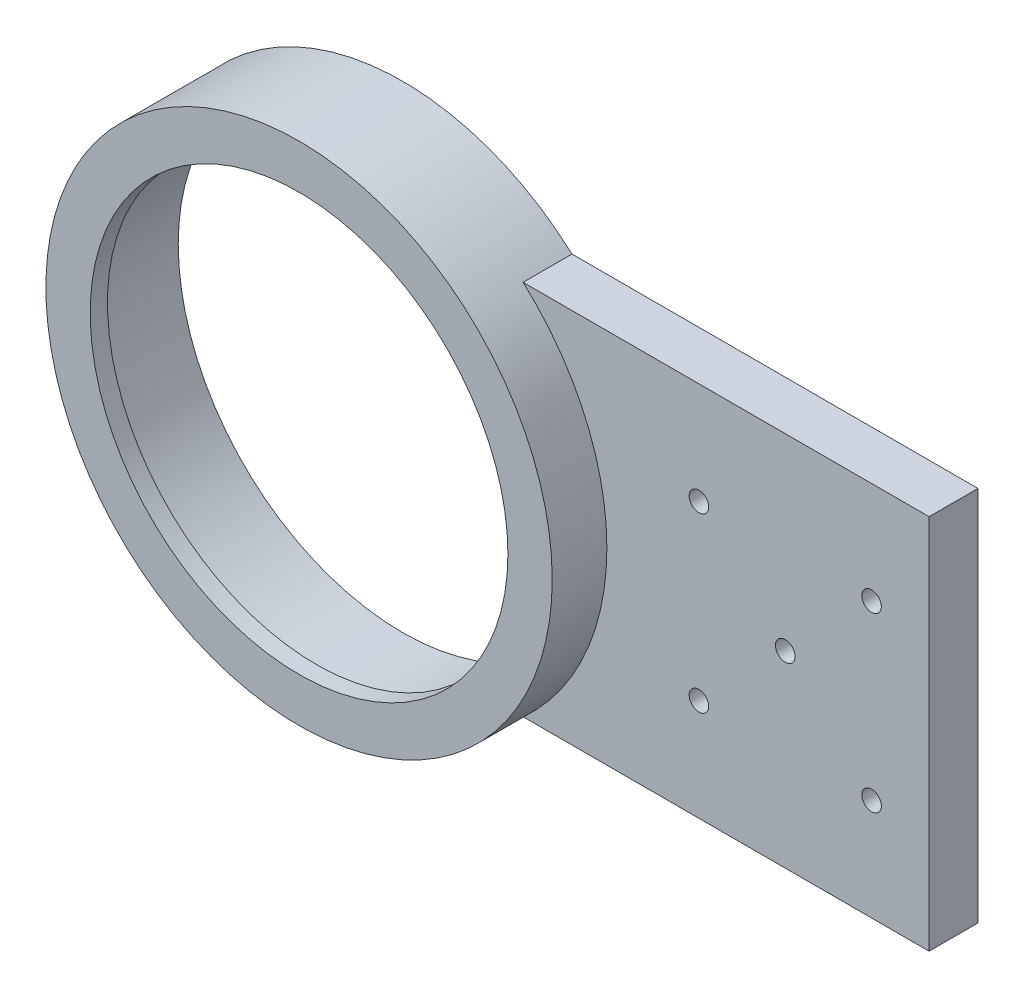
SolidWorks part; units mm, degrees
material "6063-T5"
ref_plane "Front" through (0, 0, 0) normal (0, 0, 1) x (1, 0, 0)
ref_plane "Top" through (0, 0, 0) normal (0, 1, 0) x (1, 0, 0)
ref_plane "Right" through (0, 0, 0) normal (1, 0, 0) x (0, 0, -1)
sketch "Croquis1" plane through (0, 0, 0) normal (0, 0, 1) x (1, 0, 0)
  circle A0 centre (0, 0) radius 36.3
  circle A1 centre (0, 0) radius 44
  dimension "D1" = 72.6
  dimension "D2" = 88
extrude "Saliente-Extruir1" add sketch "Croquis1" along normal blind 3
sketch "Croquis2" plane through (0, 0, 0) normal (0, 0, -1) x (-1, 0, 0)
  circle A0 centre (0, 0) radius 39
  circle A1 centre (0, 0) radius 44 construction
  circle A2 centre (0, 0) radius 44
  dimension "D1" = 78
extrude "Saliente-Extruir2" add sketch "Croquis2" along normal blind 15
sketch "Croquis3" plane through (0, 0, -15) normal (0, 0, -1) x (-1, 0, 0)
  line L0 (-29.4399, 32.7) -> (-100, 32.7)
  line L1 (-100, 32.7) -> (-100, -32.7)
  line L2 (-100, -32.7) -> (-29.4399, -32.7)
  line L3 (10.5108, 0) -> (-10.5108, 0) construction
  line L4 (0, 10.5108) -> (0, -10.5108) construction
  circle A0 centre (0, 0) radius 44 construction
  arc A1 (-29.4399, 32.7) -> (-29.4399, -32.7) centre (0, 0) ccw
  point P9 (-100, 0)
  dimension "D1" = 65.4
  dimension "D2" = 100
extrude "Saliente-Extruir3" add sketch "Croquis3" against normal blind 8.5
hole_wizard "Taladro de margen para M31" positions "Croquis4" profile "Croquis5" hole size "M3" standard "Ansi Metric" end condition up to next
sketch "Croquis4" plane through (0, 0, -15) normal (0, 0, -1) x (-1, 0, 0)
  line L1 (-60, -15) -> (-90, -15) construction
  line L2 (-60, -15) -> (-60, 15) construction
  line L3 (-60, 15) -> (-90, 15) construction
  line L4 (-90, -15) -> (-90, 15) construction
  line L5 (-60, -15) -> (-90, 15) construction
  line L6 (-60, 15) -> (-90, -15) construction
  line L7 (9.9, 0) -> (-9.9, 0) construction
  line L8 (-100, 32.7) -> (-100, -32.7) construction
  point P1 (-75, 0)
  point P2 (-90, 15)
  point P35 (-60, -15)
  point P36 (-60, 15)
  point P37 (-90, -15)
  dimension "D1" = 30
  dimension "D2" = 25
sketch "Croquis5" plane through (75, 0, -15) normal (1, 0, 0) x (0, 1, 0)
  line L0 (0, 0) -> (0, 8.5)
  line L1 (0, 8.5) -> (1.7, 8.5)
  line L2 (1.7, 8.5) -> (1.7, 0)
  line L5 (1.7, 0) -> (0, 0)
  line L11 (0, -6.35) -> (0, 107.95) construction
  dimension "Diámetro de taladro hasta el siguiente" = 3.4
  dimension "Profundidad de taladro hasta el siguiente" = 8.5
